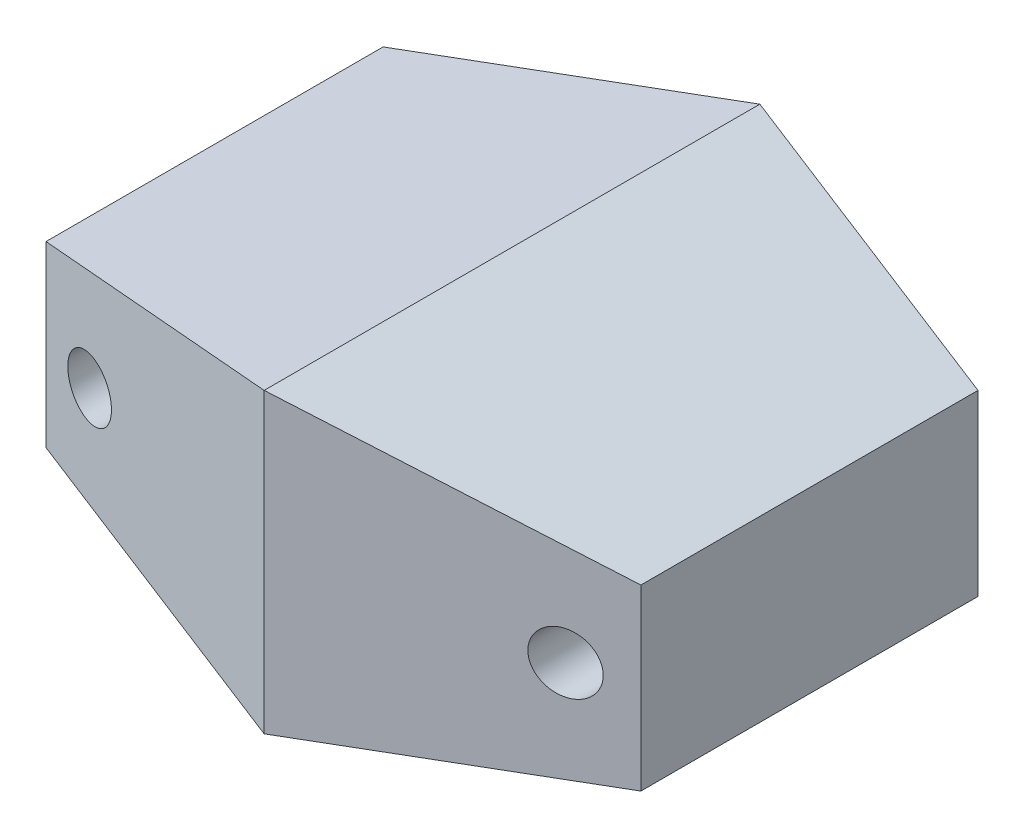
SolidWorks part; units mm, degrees
ref_plane "Front Plane" through (0, 0, 0) normal (0, 0, 1) x (1, 0, 0)
ref_plane "Top Plane" through (0, 0, 0) normal (0, 1, 0) x (1, 0, 0)
ref_plane "Right Plane" through (0, 0, 0) normal (1, 0, 0) x (0, 0, -1)
sketch "Sketch1" plane through (0, 0, 0) normal (0, 0, 1) x (1, 0, 0)
  line L1 (-30, -15) -> (30, -15)
  line L2 (-30, -15) -> (-30, 15)
  line L3 (-30, 15) -> (30, 15)
  line L4 (30, -15) -> (30, 15)
  line L5 (-30, -15) -> (30, 15) construction
  line L6 (-30, 15) -> (30, -15) construction
  point P0 (0, 0)
  dimension "D1" = 60
  dimension "D2" = 30
extrude "Boss-Extrude1" add sketch "Sketch1" along normal blind 50
sketch "Sketch2" plane through (0, 0, 50) normal (0, 0, 1) x (1, 0, 0)
  line L0 (0, 0) -> (0, 18.7839) construction
  line L1 (0, 0) -> (33.3968, 0) construction
  line L2 (0, 15) -> (-30, 9)
  line L3 (30, 15) -> (-30, 15) construction
  line L4 (-30, 15) -> (-30, -15) construction
  line L5 (0, 15) -> (30, 9)
  line L6 (0, -15) -> (30, -9)
  line L7 (0, -15) -> (-30, -9)
  line L8 (-30, 9) -> (-30, 15)
  line L9 (-30, 15) -> (0, 15)
  line L10 (0, 15) -> (30, 15)
  line L11 (30, 15) -> (30, 9)
  line L12 (30, -9) -> (30, -15)
  line L13 (30, -15) -> (0, -15)
  line L14 (-30, -9) -> (-30, -15)
  line L15 (-30, -15) -> (0, -15)
  line M5 (30, -15) -> (30, 15)
  line M6 (30, 15) -> (-30, 15)
  line M7 (-30, 15) -> (-30, -15)
  line M8 (-30, -15) -> (30, -15)
  dimension "D1" = 6
extrude "Cut-Extrude1" cut sketch "Sketch2" against normal blind 50 contours L2 M6 M7 | L5 M6 M5 | L7 M8 M7 | L6 M8 M5
sketch "Sketch4" plane through (0, 0, 0) normal (0, 1, 0) x (1, 0, 0)
  line L0 (0, -50) -> (-30, -42)
  line L1 (-30, 0) -> (-30, -50) construction
  line L2 (0, -25) -> (30.6184, -25) construction
  line L3 (0, 0) -> (0, -50) construction
  line L4 (0, -25) -> (0, 1.2753) construction
  line L5 (0, -50) -> (-30, -50) construction
  line L6 (0, -50) -> (30, -42)
  line L7 (0, 0) -> (30, -8)
  line L8 (0, 0) -> (-30, -8)
  line L9 (-30, -8) -> (-30, 0)
  line L10 (-30, 0) -> (0, 0)
  line L11 (0, 0) -> (30, 0)
  line L12 (30, 0) -> (30, -8)
  line L13 (30, -42) -> (30, -50)
  line L14 (30, -50) -> (0, -50)
  line L15 (-30, -42) -> (-30, -50)
  line L16 (-30, -50) -> (0, -50)
  dimension "D1" = 8
extrude "Cut-Extrude2" cut sketch "Sketch4" against normal through all both and the other way through all contours L10 L9 L8 | L12 L11 L7 | L14 L13 L6 | L15 L16 L0
sketch "Sketch5" plane through (0, 0, 0) normal (0, 0, 1) x (1, 0, 0)
  line L0 (-30, -9) -> (-30, 9) construction
  line L1 (0, 0) -> (0, 3.3656) construction
  line L2 (0, -15) -> (0, 15) construction
  circle A0 centre (-24, 0) radius 3
  circle A1 centre (24, 0) radius 3
  dimension "D1" = 6
extrude "Cut-Extrude4" cut sketch "Sketch5" against normal through all and the other way through all
